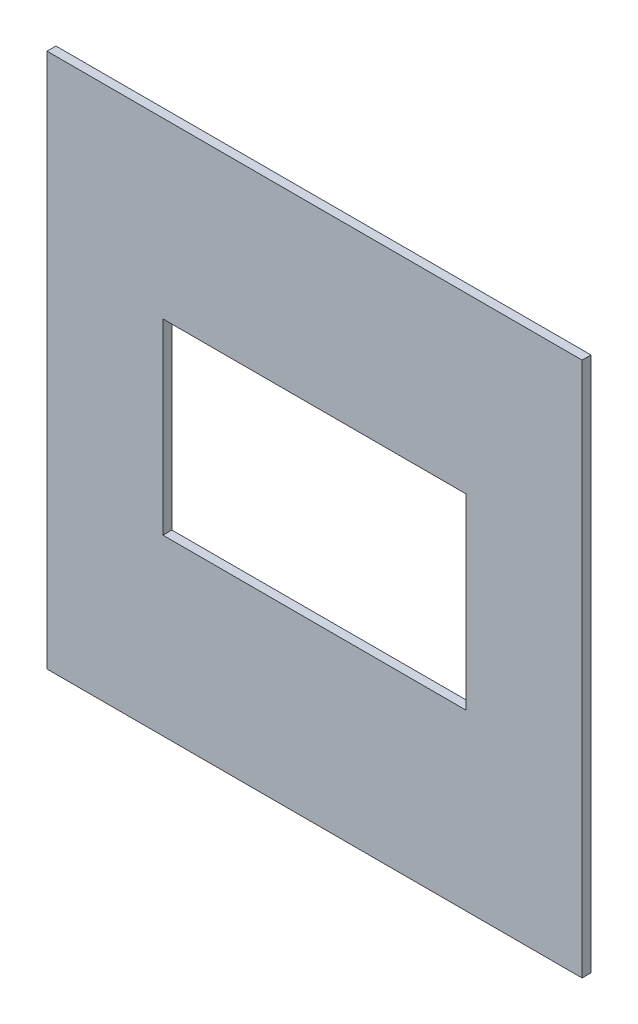
SolidWorks part; units mm, degrees
material "Hêtre"
ref_plane "Plan de face" through (0, 0, 0) normal (0, 0, 1) x (1, 0, 0)
ref_plane "Plan de dessus" through (0, 0, 0) normal (0, 1, 0) x (1, 0, 0)
ref_plane "Plan de droite" through (0, 0, 0) normal (1, 0, 0) x (0, 0, -1)
sketch "Esquisse1" plane through (0, 0, 0) normal (0, 0, 1) x (1, 0, 0)
  line L0 (0, 0) -> (300, 0)
  line L1 (300, 0) -> (300, 300)
  line L2 (300, 300) -> (0, 300)
  line L3 (0, 300) -> (0, 0)
  dimension "D1" = 300
  dimension "D2" = 300
extrude "Boss.-Extru.2" add sketch "Esquisse1" along normal blind 5
sketch "Esquisse2" plane through (0, 0, 5) normal (0, 0, 1) x (1, 0, 0)
  line L0 (65, 97.5) -> (65, 202.5)
  line L1 (65, 202.5) -> (235, 202.5)
  line L2 (235, 202.5) -> (235, 97.5)
  line L3 (235, 97.5) -> (65, 97.5)
  line L4 (0, 0) -> (300, 0) construction
  line L5 (0, 300) -> (0, 0) construction
  dimension "D1" = 105
  dimension "D2" = 170
  dimension "D3" = 97.5
  dimension "D4" = 65
extrude "Enlèv. mat.-Extru.1" cut sketch "Esquisse2" against normal blind 5 contours L1 L2 L3 L0
